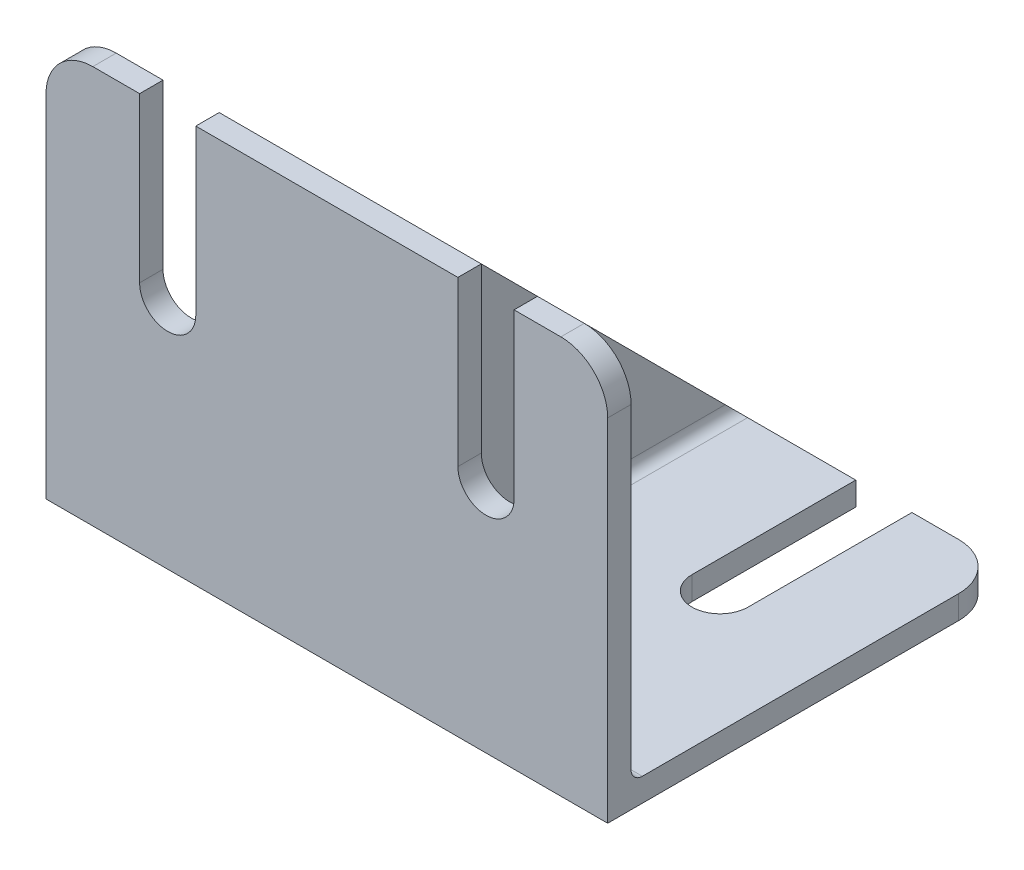
SolidWorks part; units mm, degrees
ref_plane "Front Plane" through (0, 0, 0) normal (0, 0, 1) x (1, 0, 0)
ref_plane "Top Plane" through (0, 0, 0) normal (0, 1, 0) x (1, 0, 0)
ref_plane "Right Plane" through (0, 0, 0) normal (1, 0, 0) x (0, 0, -1)
sketch "Sketch1" plane through (0, 0, 0) normal (1, 0, 0) x (0, 0, -1)
  line L0 (50.8, 0) -> (0, 0)
  line L1 (0, 0) -> (0, 50.8)
  dimension "D1" = 50.8
extrude "Extrude-Thin1" add sketch "Sketch1" along normal blind 76.2 thin thin type one direction reverse wall 3.175
fillet "Fillet1" radius 6.35 4 edges at (0, -1.5875, -50.8) (76.2, -1.5875, -50.8) (0, 50.8, 1.5875) (76.2, 50.8, 1.5875)
ref_plane "Plane1" through (0, 25.4, -25.4) normal (0, -0.7071, 0.7071) x (1, 0, 0)
sketch "Sketch2" plane through (0, 25.4, -25.4) normal (0, -0.7071, 0.7071) x (1, 0, 0)
  line L0 (38.1, -35.921) -> (38.1, 35.921) construction
  line L1 (69.85, -35.921) -> (6.35, -35.921) construction
  line L2 (69.85, 35.921) -> (6.35, 35.921) construction
  line L4 (36.5125, -35.921) -> (39.6875, -35.921)
  line L5 (36.5125, -35.921) -> (36.5125, 35.921)
  line L6 (36.5125, 35.921) -> (39.6875, 35.921)
  line L7 (39.6875, -35.921) -> (39.6875, 35.921)
  line L8 (36.5125, -35.921) -> (39.6875, 35.921) construction
  line L9 (36.5125, 35.921) -> (39.6875, -35.921) construction
  point P6 (38.1, 0)
  dimension "D1" = 3.175
extrude "Boss-Extrude1" add sketch "Sketch2" along normal up to next
sketch "Sketch3" plane through (0, 0, 0) normal (0, 0, 1) x (1, 0, 0)
  line L0 (16.51, 28.575) -> (16.51, 73.025) construction
  line L3 (12.7, 28.575) -> (12.7, 73.025)
  line L4 (20.32, 28.575) -> (20.32, 73.025)
  line L5 (59.69, 28.575) -> (59.69, 73.025) construction
  line L6 (38.1, 50.8) -> (38.1, 68.562) construction
  line L7 (39.6875, 50.8) -> (36.5125, 50.8) construction
  line L8 (63.5, 28.575) -> (63.5, 73.025)
  line L9 (55.88, 28.575) -> (55.88, 73.025)
  line L10 (16.51, 24.765) -> (16.51, 0) construction
  line L11 (36.5125, 0) -> (0, 0) construction
  arc A0 (12.7, 28.575) -> (20.32, 28.575) centre (16.51, 28.575) ccw
  arc A1 (20.32, 73.025) -> (12.7, 73.025) centre (16.51, 73.025) ccw
  arc A2 (63.5, 28.575) -> (55.88, 28.575) centre (59.69, 28.575) cw
  arc A3 (55.88, 73.025) -> (63.5, 73.025) centre (59.69, 73.025) cw
  point P2 (16.51, 50.8)
  point P9 (59.69, 50.8)
  dimension "D1" = 7.62
  dimension "D2" = 44.45
  dimension "D3" = 50.8
  dimension "D4" = 16.51
extrude "Cut-Extrude1" cut sketch "Sketch3" along normal through all
sketch "Sketch4" plane through (0, 0, 0) normal (0, 1, 0) x (1, 0, 0)
  line L0 (16.51, 73.025) -> (16.51, 28.575) construction
  line L1 (20.32, 73.025) -> (20.32, 28.575)
  line L2 (12.7, 73.025) -> (12.7, 28.575)
  line L3 (38.1, 50.8) -> (38.1, 71.8291) construction
  line L4 (36.5125, 50.8) -> (39.6875, 50.8) construction
  line L5 (59.69, 73.025) -> (59.69, 28.575) construction
  line L6 (55.88, 73.025) -> (55.88, 28.575)
  line L7 (63.5, 73.025) -> (63.5, 28.575)
  arc A0 (20.32, 73.025) -> (12.7, 73.025) centre (16.51, 73.025) ccw
  arc A1 (12.7, 28.575) -> (20.32, 28.575) centre (16.51, 28.575) ccw
  arc A2 (55.88, 73.025) -> (63.5, 73.025) centre (59.69, 73.025) cw
  arc A3 (63.5, 28.575) -> (55.88, 28.575) centre (59.69, 28.575) cw
  point P2 (16.51, 50.8)
  point P14 (59.69, 50.8)
  dimension "D1" = 7.62
  dimension "D2" = 44.45
  dimension "D3" = 50.8
  dimension "D4" = 16.51
extrude "Cut-Extrude2" cut sketch "Sketch4" against normal through all
fillet "Fillet2" radius 1.524 6 edges at (39.6875, 25.4, 0) (57.9438, 0, 0) (39.6875, 0, -25.4) (36.5125, 25.4, 0) (36.5125, 0, -25.4) (18.2563, 0, 0)
